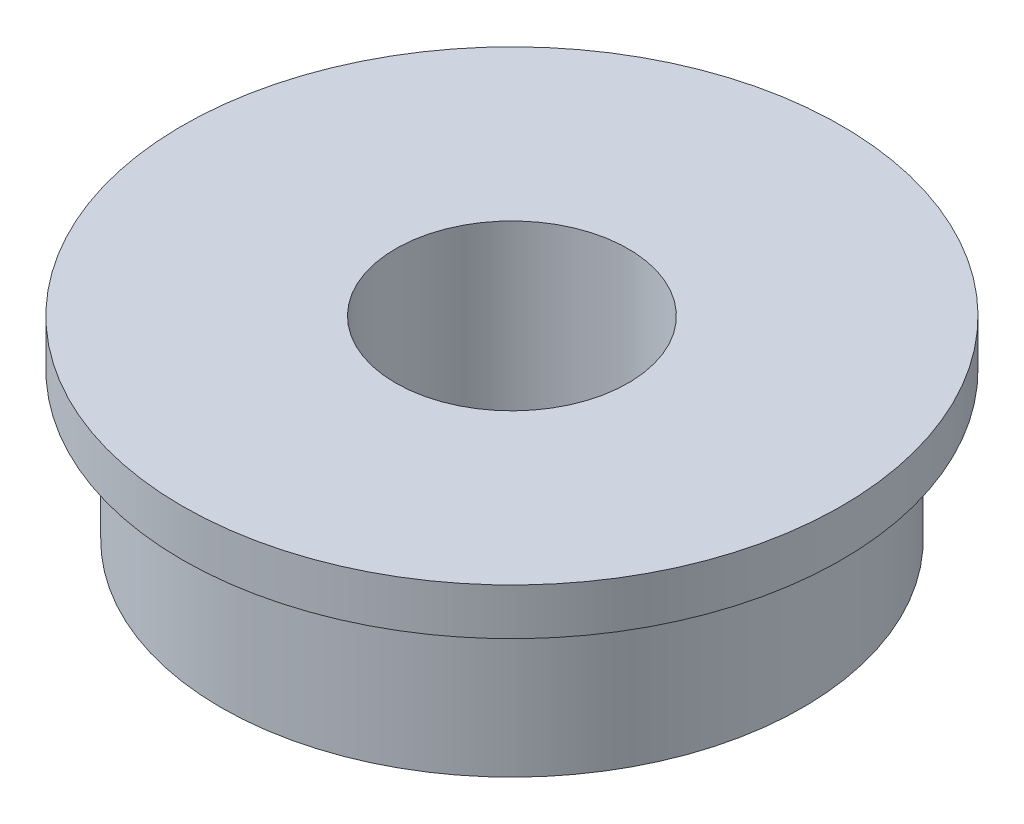
SolidWorks part; units mm, degrees
material "AISI 304"
ref_plane "前视基准面" through (0, 0, 0) normal (0, 0, 1) x (1, 0, 0)
ref_plane "上视基准面" through (0, 0, 0) normal (0, 1, 0) x (1, 0, 0)
ref_plane "右视基准面" through (0, 0, 0) normal (1, 0, 0) x (0, 0, -1)
sketch "草图1" plane through (0, 0, 0) normal (0, 0, 1) x (1, 0, 0)
  line L0 (0, 3.8119) -> (0, 0) construction
  line L1 (0, 0) -> (7.5, 0) construction
  line L2 (3, 0) -> (7.5, 0)
  line L3 (7.5, 0) -> (7.5, 3.8)
  line L4 (7.5, 3.8) -> (8.5, 3.8)
  line L5 (8.5, 3.8) -> (8.5, 5)
  line L6 (8.5, 5) -> (3, 5)
  line L7 (3, 5) -> (3, 0)
  dimension "D1" = 6
  dimension "D2" = 15
  dimension "D3" = 5
  dimension "D4" = 1.2
  dimension "D5" = 17
revolve "旋转1" add sketch "草图1" angle 360 about L0
